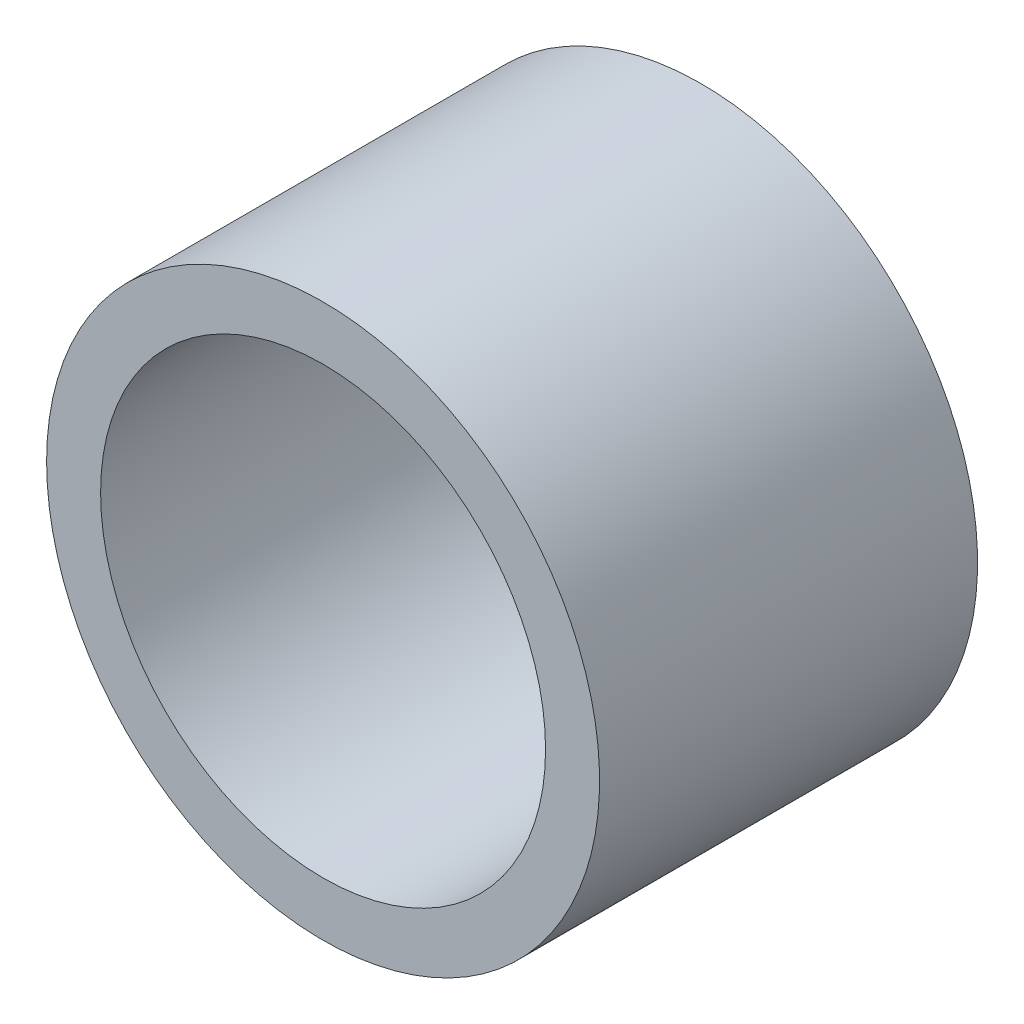
SolidWorks part; units mm, degrees
material "6061-T6 (SS)"
ref_plane "Front Plane" through (0, 0, 0) normal (0, 0, 1) x (1, 0, 0)
ref_plane "Top Plane" through (0, 0, 0) normal (0, 1, 0) x (1, 0, 0)
ref_plane "Right Plane" through (0, 0, 0) normal (1, 0, 0) x (0, 0, -1)
sketch "Sketch1" plane through (0, 0, 0) normal (1, 0, 0) x (0, 0, -1)
  line L0 (0, 26.162) -> (0, 32.512)
  line L3 (0, 32.512) -> (-44.45, 32.512)
  line L4 (-44.45, 32.512) -> (-44.45, 26.162)
  line L5 (-44.45, 26.162) -> (0, 26.162)
  line L6 (0, 0) -> (-50000, 0) construction
  dimension "D1" = 65.024
  dimension "D3" = 44.45
  dimension "D5" = 52.324
revolve "Revolve1" add sketch "Sketch1" angle 360 about L6
